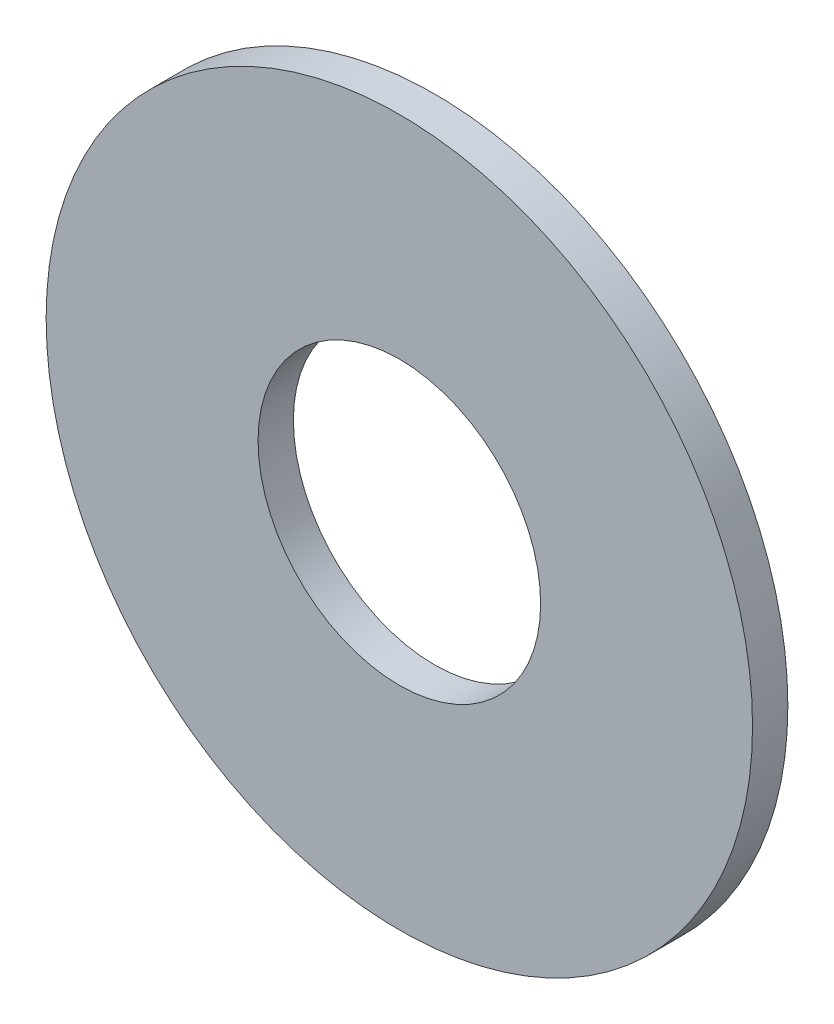
SolidWorks part; units mm, degrees
material "1.0503 (C45)"
ref_plane "前视基准面" through (0, 0, 0) normal (0, 0, 1) x (1, 0, 0)
ref_plane "上视基准面" through (0, 0, 0) normal (0, 1, 0) x (1, 0, 0)
ref_plane "右视基准面" through (0, 0, 0) normal (1, 0, 0) x (0, 0, -1)
other "Configuration Table"
sketch "草图1" plane through (0, 0, 0) normal (0, 0, 1) x (1, 0, 0)
  line L0 (-9.098, 0) -> (2.1323, 0) construction
  line L1 (0, 3.9004) -> (0, -3.1541) construction
  circle A0 centre (0, 0) radius 2
  circle A1 centre (0, 0) radius 5
  dimension "D1" = 4
  dimension "D2" = 10
extrude "凸台-拉伸1" add sketch "草图1" along normal blind 0.5
